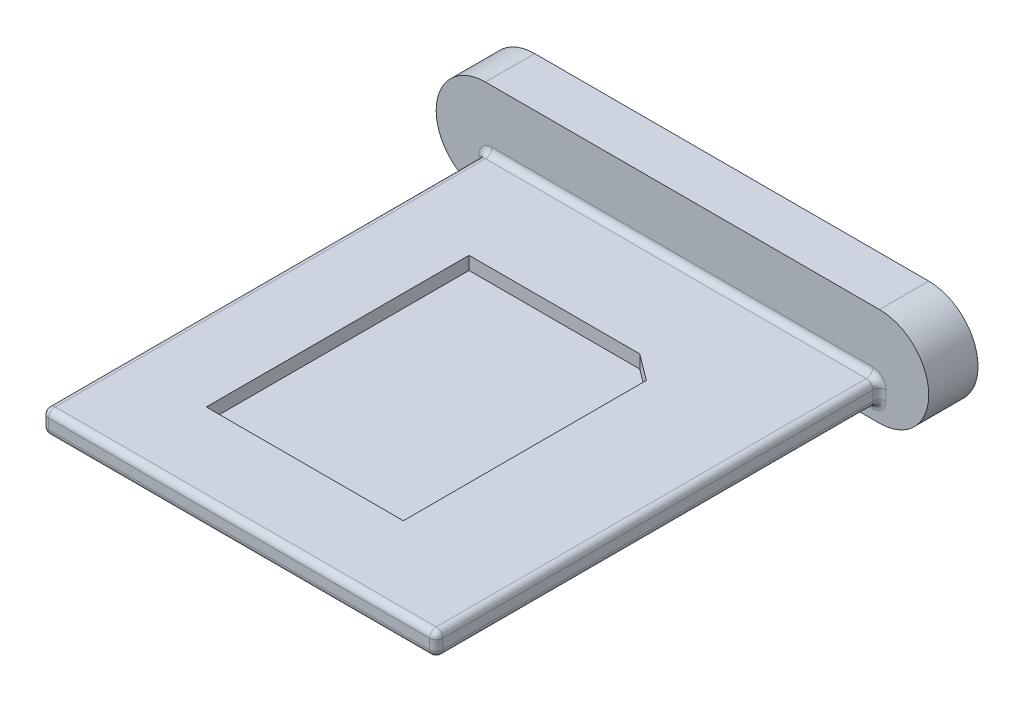
SolidWorks part; units mm, degrees
ref_plane "前视基准面" through (0, 0, 0) normal (0, 0, 1) x (1, 0, 0)
ref_plane "上视基准面" through (0, 0, 0) normal (0, 1, 0) x (1, 0, 0)
ref_plane "右视基准面" through (0, 0, 0) normal (1, 0, 0) x (0, 0, -1)
other "Configuration Table"
sketch "草图1" plane through (0, 0, 0) normal (0, 0, 1) x (1, 0, 0)
  line L1 (-5.3717, 2.0469) -> (6.6283, 2.0469)
  line L3 (-5.3717, -0.9531) -> (6.6283, -0.9531)
  arc A0 (-5.3717, 2.0469) -> (-5.3717, -0.9531) centre (-5.3717, 0.5469) ccw
  arc A1 (6.6283, 2.0469) -> (6.6283, -0.9531) centre (6.6283, 0.5469) cw
  dimension "D1" = 12
  dimension "D2" = 3
extrude "凸台-拉伸3" add sketch "草图1" along normal blind 1.5 contours L1 A1 L3 A0
sketch "草图2" plane through (0, 0, 1.5) normal (0, 0, 1) x (1, 0, 0)
  line L2 (-5.3717, -0.0729) -> (-5.3717, 0.2271)
  line L4 (-5.3717, -0.0729) -> (-5.3717, -0.4729)
  line L5 (-5.3717, -0.4729) -> (6.6283, -0.4729)
  line L6 (6.6283, -0.0729) -> (6.6283, -0.4729)
  line L7 (-5.3717, 0.2271) -> (6.6283, 0.2271)
  line L8 (6.6283, -0.0729) -> (6.6283, 0.2271)
  dimension "D1" = 0.4
  dimension "D2" = 0.3
extrude "凸台-拉伸4" add sketch "草图2" along normal blind 13.5
sketch "草图3" plane through (0, 0.2271, 0) normal (0, 1, 0) x (1, 0, 0)
  line L2 (-2.8717, -4.5) -> (-2.8717, -12.5)
  line L3 (-2.8717, -12.5) -> (3.1283, -12.5)
  line L13 (3.1283, -5.1) -> (1.7846, -4.5)
  line L15 (-2.8717, -4.5) -> (1.7846, -4.5)
  line L16 (3.1283, -12.5) -> (3.1283, -5.1)
  dimension "D2" = 8
extrude "切除-拉伸2" cut sketch "草图3" against normal blind 0.4 contours L2 L3 L16 L13 L15
fillet "圆角2" radius 0.2 12 edges at (0.6283, 0.2271, 1.5) (0.6283, -0.4729, 1.5) (6.6283, -0.4729, 8.25) (6.6283, 0.2271, 8.25) (6.6283, -0.1229, 1.5) (0.6283, -0.4729, 15) (0.6283, 0.2271, 15) (6.6283, -0.1229, 15) (-5.3717, 0.2271, 8.25) (-5.3717, -0.1229, 15) (-5.3717, -0.4729, 8.25) (-5.3717, -0.1229, 1.5)
sketch "草图4" plane through (0, 0.2271, 0) normal (0, 1, 0) x (1, 0, 0)
  line L0 (-2.8717, -12.5) -> (-2.8717, -4.5)
  line L1 (-2.8717, -12.5) -> (3.1283, -12.5)
  line L2 (3.1283, -12.5) -> (3.1283, -5.1)
  line L3 (-2.8717, -4.5) -> (2.3283, -4.5)
  line L4 (3.1283, -5.1) -> (2.3283, -4.5)
extrude "切除-拉伸3" cut sketch "草图4" against normal blind 0.4
